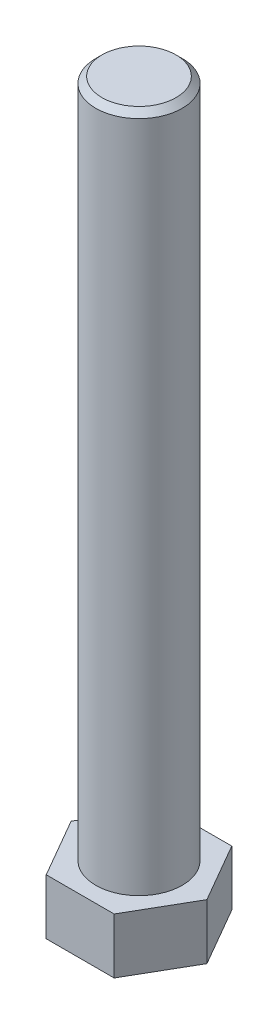
SolidWorks part; units mm, degrees
ref_plane "Alzado" through (0, 0, 0) normal (0, 0, 1) x (1, 0, 0)
ref_plane "Planta" through (0, 0, 0) normal (0, 1, 0) x (1, 0, 0)
ref_plane "Vista lateral" through (0, 0, 0) normal (1, 0, 0) x (0, 0, -1)
sketch "Croquis1" plane through (0, 0, 0) normal (0, 1, 0) x (1, 0, 0)
  line L0 (-11, 0) -> (11, 0) construction
  line L1 (11, 0) -> (5.5, 9.5263)
  line L2 (5.5, 9.5263) -> (-5.5, 9.5263)
  line L3 (-5.5, 9.5263) -> (-11, 0)
  line L4 (-11, 0) -> (-5.5, -9.5263)
  line L5 (-5.5, -9.5263) -> (5.5, -9.5263)
  line L6 (5.5, -9.5263) -> (11, 0)
  circle A0 centre (0, 0) radius 9.5263 construction
  dimension "D1" = 22
extrude "Saliente-Extruir1" add sketch "Croquis1" along normal blind 8.98
sketch "Croquis2" plane through (0, 8.98, 0) normal (0, 1, 0) x (1, 0, 0)
  circle A0 centre (0, 0) radius 7
  dimension "D1" = 14
extrude "Saliente-Extruir3" add sketch "Croquis2" along normal blind 110
chamfer "Chaflán4" distance 1 angle 45 1 edges at (0, 118.98, 7)
